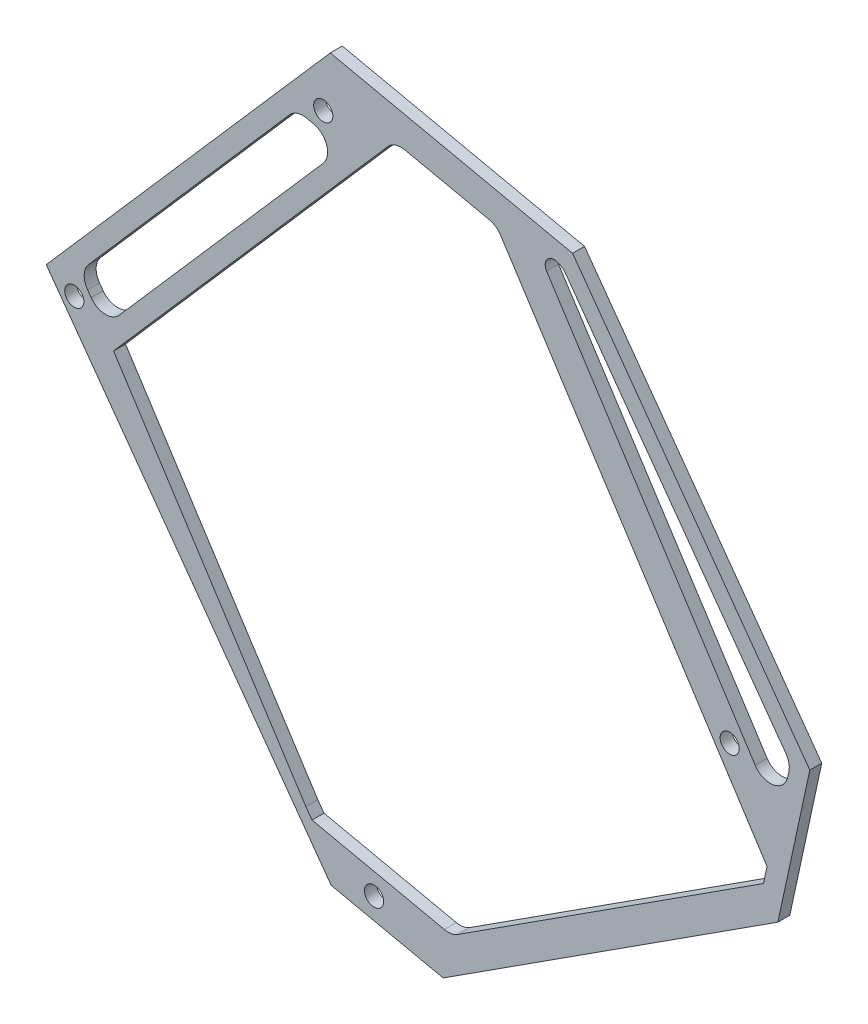
SolidWorks part; units mm, degrees
ref_plane "Front Plane" through (0, 0, 0) normal (0, 0, 1) x (1, 0, 0)
ref_plane "Top Plane" through (0, 0, 0) normal (0, 1, 0) x (1, 0, 0)
ref_plane "Right Plane" through (0, 0, 0) normal (1, 0, 0) x (0, 0, -1)
sketch "Sketch2" plane through (0, 0, 0) normal (0, 0, 1) x (1, 0, 0)
  line L0 (73.9376, -53.6324) -> (139.3345, -11.4889) construction
  line L1 (23.0052, 15.0711) -> (78.8501, -62.3632) construction
  line L2 (20.3423, 18.7634) -> (67.8353, 73.1631)
  line L3 (20.3423, 18.7634) -> (75.9214, -58.3023)
  line L4 (67.8353, 73.1631) -> (108.342, 64.4044)
  line L5 (108.342, 64.4044) -> (148.0067, 9.4055)
  line L6 (148.0067, 9.4055) -> (142.6668, -15.2898)
  line L7 (142.6668, -15.2898) -> (75.9214, -58.3023)
  line L8 (137.0563, 6.0793) -> (129.2848, -29.8618) construction
  line L9 (136.6405, 8.07) -> (99.4769, 59.6009) construction
  line L10 (93.4796, 63.5256) -> (8.7498, 81.8467) construction
  line L11 (140.2592, -10.8931) -> (140.8569, -8.1285)
  line L12 (31.5961, 11.887) -> (63.751, -38.0098)
  line L15 (78.5952, 65.721) -> (31.5961, 11.887)
  line L17 (29.3265, 15.4089) -> (66.3782, -42.0866) construction
  line L18 (70.5208, -33.6472) -> (64.4234, -37.5765) construction
  line L19 (63.751, -38.0098) -> (74.6751, -53.1572)
  line L20 (74.6751, -53.1572) -> (140.2592, -10.8931)
  line L21 (78.5952, 65.721) -> (95.6417, 62.035)
  line L22 (95.6417, 62.035) -> (140.8569, -8.1285)
  line L23 (139.5139, -10.6596) -> (85.9948, 72.3895) construction
  circle A0 centre (25.0329, 16.5335) radius 1.6 construction
  circle A1 centre (66.6563, 64.2101) radius 2.5 construction
  circle A3 centre (25.0329, 16.5335) radius 1.6
  circle A4 centre (66.6563, 64.2101) radius 1.6
  circle A5 centre (134.6128, 6.6076) radius 1.6
  point P32 (141.9403, -9.8097)
  point P41 (95.832, 61.7397)
  dimension "D1" = 5
  dimension "D2" = 5
  dimension "D5" = 5
  dimension "D7" = 3.2
  dimension "D3" = 4
  dimension "D4" = 10
  dimension "D6" = 10
  dimension "D8" = 2.5
  dimension "D9" = 5
  dimension "D10" = 13
extrude "Boss-Extrude1" add sketch "Sketch2" along normal blind 2
chamfer "Chamfer1" distance 16 angle 45 1 edges at (74.6751, -53.1572, 1)
sketch "Sketch3" plane through (0, 0, 2) normal (0, 0, 1) x (1, 0, 0)
  line L0 (67.9845, -47.2971) -> (86.7144, -51.347)
  line L1 (20.3423, 18.7634) -> (75.9214, -58.3023) construction
  line L2 (75.9214, -58.3023) -> (142.6668, -15.2898) construction
  line L3 (86.7144, -51.347) -> (75.9214, -58.3023)
  line L4 (75.9214, -58.3023) -> (67.9845, -47.2971)
  line L5 (69.7354, -46.1332) -> (82.5458, -37.8778) construction
  line L6 (88.1243, -44.4901) -> (64.7849, -39.4434) construction
  point P10 (76.1406, -42.0055)
  dimension "D1" = 7
extrude "Cut-Extrude1" cut sketch "Sketch3" against normal blind 2
sketch "Sketch4" plane through (0, 0, 2) normal (0, 0, 1) x (1, 0, 0)
  line L0 (25.8574, 20.5189) -> (30.061, 14.6902)
  line L1 (30.061, 14.6902) -> (69.9856, 60.4208)
  line L2 (69.9856, 60.4208) -> (62.1688, 62.111)
  line L3 (62.1688, 62.111) -> (25.8574, 20.5189)
  line L4 (20.3423, 18.7634) -> (67.9845, -47.2971) construction
  line L5 (67.8353, 73.1631) -> (20.3423, 18.7634) construction
  line L6 (78.5952, 65.721) -> (31.5961, 11.887) construction
  line L7 (108.342, 64.4044) -> (67.8353, 73.1631) construction
  line L8 (102.0352, 62.6988) -> (106.5823, 61.7155)
  line L9 (106.5823, 61.7155) -> (144.7921, 8.734)
  line L10 (144.7921, 8.734) -> (142.7871, -0.5387)
  line L11 (142.7871, -0.5387) -> (102.0352, 62.6988)
  line L12 (140.8569, -8.1285) -> (95.6417, 62.035) construction
  line L13 (148.0067, 9.4055) -> (108.342, 64.4044) construction
  line L14 (142.6668, -15.2898) -> (148.0067, 9.4055) construction
  circle A0 centre (25.0329, 16.5335) radius 1.5 construction
  circle A1 centre (66.6563, 64.2101) radius 2.5 construction
  circle A2 centre (134.6128, 6.6076) radius 1.5 construction
  dimension "D1" = 3
  dimension "D2" = 3
  dimension "D3" = 3
  dimension "D4" = 3
  dimension "D5" = 3
  dimension "D6" = 3
  dimension "D7" = 3
  dimension "D8" = 3
extrude "Cut-Extrude2" cut sketch "Sketch4" against normal blind 2
fillet "Fillet1" radius 3 10 edges at (88.1243, -44.4901, 1) (95.6417, 62.035, 1) (78.5952, 65.721, 1) (30.061, 14.6902, 1) (25.8574, 20.5189, 1) (62.1688, 62.111, 1) (69.9856, 60.4208, 1) (142.7871, -0.5387, 1) (144.7921, 8.734, 1) (106.5823, 61.7155, 1)
fillet "Fillet2" radius 1.5 1 edges at (102.0352, 62.6988, 1)
sketch "Sketch5" plane through (0, 0, 2) normal (0, 0, 1) x (1, 0, 0)
  line L0 (86.7144, -51.347) -> (67.9845, -47.2971) construction
  line L1 (20.3423, 18.7634) -> (67.9845, -47.2971) construction
  circle A0 centre (75.1499, -45.2656) radius 1.6
  dimension "D1" = 3.2
  dimension "D2" = 3.5
  dimension "D3" = 7
extrude "Cut-Extrude3" cut sketch "Sketch5" against normal blind 2
